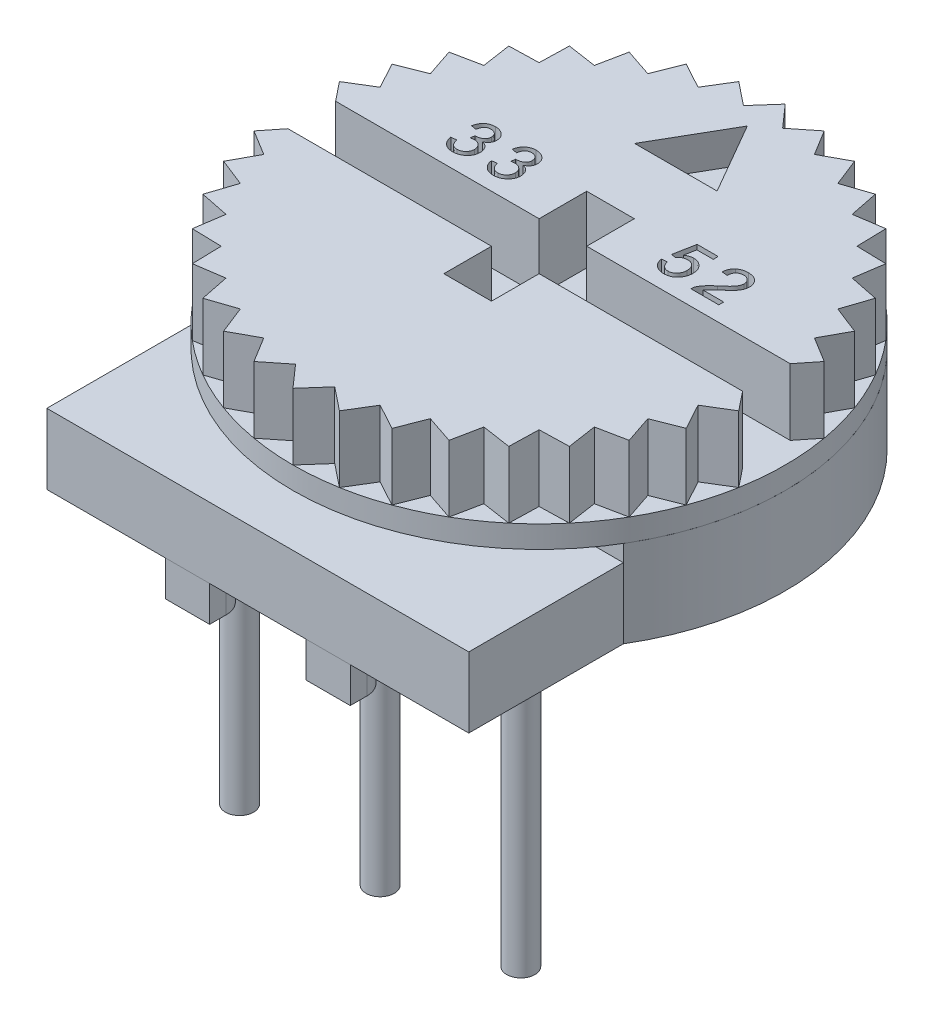
SolidWorks part; units mm, degrees
ref_plane "Спереди" through (0, 0, 0) normal (0, 0, 1) x (1, 0, 0)
ref_plane "Сверху" through (0, 0, 0) normal (0, 1, 0) x (1, 0, 0)
ref_plane "Справа" through (0, 0, 0) normal (1, 0, 0) x (0, 0, -1)
sketch "Эскиз1" plane through (0, 0, 0) normal (0, 1, 0) x (1, 0, 0)
  line L0 (0, 0) -> (0, -4.7821) construction
  line L3 (-3.81, -2.2895) -> (-3.81, -5.08)
  line L4 (-3.81, -5.08) -> (3.81, -5.08)
  line L5 (3.81, -2.2895) -> (3.81, -5.08)
  arc A0 (3.81, -2.2895) -> (-3.81, -2.2895) centre (0, 0) ccw
  dimension "D1" = 8.89
  dimension "D2" = 5.08
  dimension "D3" = 7.62
extrude "Бобышка-Вытянуть1" add sketch "Эскиз1" along normal blind 1.27 from offset 0.64
sketch "Эскиз2" plane through (0, 1.91, 1.91) normal (0, 1, 0) x (1, 0, 0)
  line L0 (0, 1.91) -> (0, 7.6224) construction
  line L1 (-3.81, -0.3795) -> (3.81, -0.3795)
  arc A0 (3.81, -0.3795) -> (-3.81, -0.3795) centre (0, 1.91) ccw
extrude "Бобышка-Вытянуть2" add sketch "Эскиз2" along normal blind 0.3
sketch "Эскиз3" plane through (0, 0, 0) normal (0, 1, 0) x (1, 0, 0)
  circle A0 centre (0, 0) radius 4.445
  arc A2 (3.81, -2.2895) -> (-3.81, -2.2895) centre (0, 0) ccw construction
  point P0 (0, 0)
extrude "Бобышка-Вытянуть3" add sketch "Эскиз3" along normal blind 1.6 from offset 2.21 separate body
sketch "Эскиз4" plane through (0, 0, 0) normal (0, 1, 0) x (1, 0, 0)
  line L0 (0, 0) -> (0, -5.2728) construction
  line L1 (-1.27, -5.08) -> (-1.27, 4) construction
  line L2 (1.27, -5.08) -> (1.27, 4) construction
  line L4 (-1.67, -4.78) -> (-1.67, -5.08)
  line L5 (0.87, -5.08) -> (1.67, -5.08)
  line L6 (-0.87, 4) -> (-0.87, 4.359)
  line L7 (0.87, 4) -> (0.87, 4.359)
  line L8 (1.638, 3.8433) -> (1.7427, 4.0891)
  line L9 (-1.6381, 3.8434) -> (-1.7426, 4.0892)
  line L10 (1.67, -5.08) -> (1.67, -4.78)
  line L11 (0.87, -5.08) -> (0.87, -4.78)
  line L12 (-0.87, -4.78) -> (-0.87, -5.08)
  line L13 (-1.67, -5.08) -> (-0.87, -5.08)
  line L14 (-3.81, -5.08) -> (3.81, -5.08) construction
  circle A0 centre (0, 0) radius 1
  circle A1 centre (0, 0) radius 4.445 construction
  arc A4 (0.87, 4) -> (1.638, 3.8433) centre (1.27, 4) ccw
  arc A5 (-1.6381, 3.8434) -> (-0.87, 4) centre (-1.27, 4) ccw
  arc A6 (-1.7426, 4.0892) -> (-0.87, 4.359) centre (0, 0) cw
  arc A7 (0.87, 4.359) -> (1.7427, 4.0891) centre (0, 0) cw
  arc A8 (-0.87, -4.78) -> (-1.67, -4.78) centre (-1.27, -4.78) ccw
  arc A9 (1.67, -4.78) -> (0.87, -4.78) centre (1.27, -4.78) ccw
  point P0 (0, 0)
  point P9 (-1.27, -5.08)
  point P10 (1.27, -5.08)
  point P29 (-1.27, -4.78)
  point P30 (1.27, -4.78)
  dimension "D1" = 2
  dimension "D3" = 0.4
  dimension "D4" = 0.3
  dimension "D5" = 0.8
  dimension "D6" = 0.8
  dimension "D11" = 0.8
  dimension "D12" = 0.8
  dimension "D2" = 1.27
  dimension "D7" = 4
  dimension "D8" = 0.3681
  dimension "D9" = 0.368
  dimension "D10" = 0.3
  dimension "D13" = 0.3
extrude "Бобышка-Вытянуть4" add sketch "Эскиз4" along normal up to surface (0.64 mm away) separate body up to face at (0, 0.64, 2.0011)
sketch "Эскиз5" plane through (0, 0, 0) normal (0, 1, 0) x (1, 0, 0)
  line L0 (0, 0) -> (0, -5.5292) construction
  line L1 (-5.2502, -2.87) -> (6.7887, -2.87) construction
  circle A0 centre (0, -2.87) radius 0.255
  circle A1 centre (-2.54, -2.87) radius 0.255
  circle A2 centre (2.54, -2.87) radius 0.255
  point P6 (0, -2.87)
  dimension "D2" = 0.51
  dimension "D4" = 0.51
  dimension "D1" = 2.87
  dimension "D3" = 2.54
extrude "Бобышка-Вытянуть5" add sketch "Эскиз5" against normal blind 4.75 and the other way up to surface (0.64 mm away) separate body other way up to face at (0, 0.64, 2.0011)
sketch "Эскиз6" plane through (0, 3.81, -3.81) normal (0, -1, 0) x (1, 0, 0)
  line L0 (0, 3.81) -> (0, -0.9945) construction
  line L1 (0, -0.635) -> (-0.3539, -0.2346)
  line L2 (0, -0.635) -> (0.3539, -0.2346)
  line L3 (-0.7719, -0.5675) -> (-0.3539, -0.2346)
  line L4 (-0.7719, -0.5675) -> (-1.0508, -0.1117)
  line L5 (-1.5203, -0.3669) -> (-1.0508, -0.1117)
  line L6 (-1.5203, -0.3669) -> (-1.7158, 0.1304)
  line L7 (-2.2225, -0.0395) -> (-1.7158, 0.1304)
  line L8 (-2.2225, -0.0395) -> (-2.3287, 0.4842)
  line L9 (-2.8572, 0.4049) -> (-2.3287, 0.4842)
  line L10 (-2.8572, 0.4049) -> (-2.8709, 0.9391)
  line L11 (-3.4051, 0.9528) -> (-2.8709, 0.9391)
  line L12 (-3.4051, 0.9528) -> (-3.3258, 1.4813)
  line L13 (-3.8495, 1.5875) -> (-3.3258, 1.4813)
  line L14 (-3.8495, 1.5875) -> (-3.6796, 2.0942)
  line L15 (-4.1769, 2.2897) -> (-3.6796, 2.0942)
  line L16 (-4.1769, 2.2897) -> (-3.9217, 2.7592)
  line L17 (-4.3775, 3.0381) -> (-3.9217, 2.7592)
  line L18 (-4.3775, 3.0381) -> (-4.1052, 3.38)
  line L21 (-4.3775, 4.5819) -> (-4.1052, 4.24)
  line L22 (-4.3775, 4.5819) -> (-3.9217, 4.8608)
  line L23 (-4.1769, 5.3303) -> (-3.9217, 4.8608)
  line L24 (-4.1769, 5.3303) -> (-3.6796, 5.5258)
  line L25 (-3.8495, 6.0325) -> (-3.6796, 5.5258)
  line L26 (-3.8495, 6.0325) -> (-3.3258, 6.1387)
  line L27 (-3.4051, 6.6672) -> (-3.3258, 6.1387)
  line L28 (-3.4051, 6.6672) -> (-2.8709, 6.6809)
  line L29 (-2.8572, 7.2151) -> (-2.8709, 6.6809)
  line L30 (-2.8572, 7.2151) -> (-2.3287, 7.1358)
  line L31 (-2.2225, 7.6595) -> (-2.3287, 7.1358)
  line L32 (-2.2225, 7.6595) -> (-1.7158, 7.4896)
  line L33 (-1.5203, 7.9869) -> (-1.7158, 7.4896)
  line L34 (-1.5203, 7.9869) -> (-1.0508, 7.7317)
  line L35 (-0.7719, 8.1875) -> (-1.0508, 7.7317)
  line L36 (-0.7719, 8.1875) -> (-0.3539, 7.8546)
  line L37 (0, 8.255) -> (-0.3539, 7.8546)
  line L38 (0, 8.255) -> (0.3539, 7.8546)
  line L39 (0.7719, 8.1875) -> (0.3539, 7.8546)
  line L40 (0.7719, 8.1875) -> (1.0508, 7.7317)
  line L41 (1.5203, 7.9869) -> (1.0508, 7.7317)
  line L42 (1.5203, 7.9869) -> (1.7158, 7.4896)
  line L43 (2.2225, 7.6595) -> (1.7158, 7.4896)
  line L44 (2.2225, 7.6595) -> (2.3287, 7.1358)
  line L45 (2.8572, 7.2151) -> (2.3287, 7.1358)
  line L46 (2.8572, 7.2151) -> (2.8709, 6.6809)
  line L47 (3.4051, 6.6672) -> (2.8709, 6.6809)
  line L48 (3.4051, 6.6672) -> (3.3258, 6.1387)
  line L49 (3.8495, 6.0325) -> (3.3258, 6.1387)
  line L50 (3.8495, 6.0325) -> (3.6796, 5.5258)
  line L51 (4.1769, 5.3303) -> (3.6796, 5.5258)
  line L52 (4.1769, 5.3303) -> (3.9217, 4.8608)
  line L53 (4.3775, 4.5819) -> (3.9217, 4.8608)
  line L54 (4.3775, 4.5819) -> (4.1052, 4.24)
  line L57 (4.3775, 3.0381) -> (4.1052, 3.38)
  line L58 (4.3775, 3.0381) -> (3.9217, 2.7592)
  line L59 (4.1769, 2.2897) -> (3.9217, 2.7592)
  line L60 (4.1769, 2.2897) -> (3.6796, 2.0942)
  line L61 (3.8495, 1.5875) -> (3.6796, 2.0942)
  line L62 (3.8495, 1.5875) -> (3.3258, 1.4813)
  line L63 (3.4051, 0.9528) -> (3.3258, 1.4813)
  line L64 (3.4051, 0.9528) -> (2.8709, 0.9391)
  line L65 (2.8572, 0.4049) -> (2.8709, 0.9391)
  line L66 (2.8572, 0.4049) -> (2.3287, 0.4842)
  line L67 (2.2225, -0.0395) -> (2.3287, 0.4842)
  line L68 (2.2225, -0.0395) -> (1.7158, 0.1304)
  line L69 (1.5203, -0.3669) -> (1.7158, 0.1304)
  line L70 (1.5203, -0.3669) -> (1.0508, -0.1117)
  line L71 (0.7719, -0.5675) -> (1.0508, -0.1117)
  line L72 (0.7719, -0.5675) -> (0.3539, -0.2346)
  line L73 (0.43, 3.38) -> (4.1052, 3.38)
  line L74 (-4.1052, 4.24) -> (-0.43, 4.24)
  line L76 (-4.1052, 3.38) -> (-0.43, 3.38)
  line L78 (-4.1052, 4.24) -> (4.1052, 3.38) construction
  line L79 (-4.1052, 3.38) -> (4.1052, 4.24) construction
  line L80 (-0.43, 5.1) -> (0.43, 5.1)
  line L81 (-0.43, 5.1) -> (-0.43, 4.24)
  line L82 (-0.43, 2.52) -> (0.43, 2.52)
  line L83 (0.43, 5.1) -> (0.43, 4.24)
  line L84 (-0.43, 5.1) -> (0.43, 2.52) construction
  line L85 (-0.43, 2.52) -> (0.43, 5.1) construction
  line L86 (0.43, 3.38) -> (0.43, 2.52)
  line L87 (-0.43, 3.38) -> (-0.43, 2.52)
  line L88 (0.43, 4.24) -> (4.1052, 4.24)
  line L90 (4.445, 3.81) -> (4.0446, 3.4561) [skipped]
  line L91 (4.445, 3.81) -> (4.0446, 4.1639) [skipped]
  line L92 (-4.445, 3.81) -> (-4.0446, 3.4561) [skipped]
  line L93 (-4.445, 3.81) -> (-4.0446, 4.1639) [skipped]
  circle A0 centre (0, 3.81) radius 4.06 construction
  circle A2 centre (0, 3.81) radius 6
  circle A3 centre (0, 3.81) radius 4.445 construction
  point P0 (0, 3.81)
  circle M101 centre (0, 3.81) radius 4.445
  dimension "D1" = 8.12
  dimension "D5" = 12
  dimension "D2" = 0.86
  dimension "D3" = 0.86
  dimension "D4" = 2.58
  dimension "D6" = 0.43
extrude "Вырез-Вытянуть1" cut sketch "Эскиз6" along normal blind 1.2 contours L83 L88 L54 L57 L73 L86 L82 L87 L76 L18 L21 L74 L81 L80 M101 | A2 M101 | L59 L58 M101 | L61 L60 M101 | L63 L62 M101 | L65 L64 M101 | L67 L66 M101 | L69 L68 M101 | L71 L70 M101 | L72 L2 M101 | L3 L1 M101 | L5 L4 M101 | L7 L6 M101 | L9 L8 M101 | L11 L10 M101 | L13 L12 M101 | L15 L14 M101 | L17 L16 M101 | L23 L22 M101 | L25 L24 M101 | L27 L26 M101 | L29 L28 M101 | L31 L30 M101 | L33 L32 M101 | L35 L34 M101 | L37 L36 M101 | L39 L38 M101 | L41 L40 M101 | L43 L42 M101 | L45 L44 M101 | L47 L46 M101 | L49 L48 M101 | L51 L50 M101 | L53 L52 M101
sketch "Эскиз7" plane through (0, 0, 0) normal (0, 1, 0) x (1, 0, 0)
  line L0 (0, 0) -> (0, 5.5627) construction
  line L2 (0, 3.76) -> (-0.7448, 2.47)
  line L3 (-0.7448, 2.47) -> (0.7448, 2.47)
  line L4 (0.7448, 2.47) -> (0, 3.76)
  circle A0 centre (0, 2.9) radius 0.43 construction
  point P0 (0, 0)
  dimension "D2" = 0.86
  dimension "D1" = 2.9
extrude "Вырез-Вытянуть2" cut sketch "Эскиз7" against normal blind 0.6 from offset 3.81
sketch "Эскиз8" plane through (0, 0, 0) normal (0, 1, 0) x (1, 0, 0)
  text T0 "33   52" font "GOST" height in points 3
  point P0 (0, 0)
extrude "Вырез-Вытянуть3" cut sketch "Эскиз8" against normal blind 0.3 from offset 3.81
